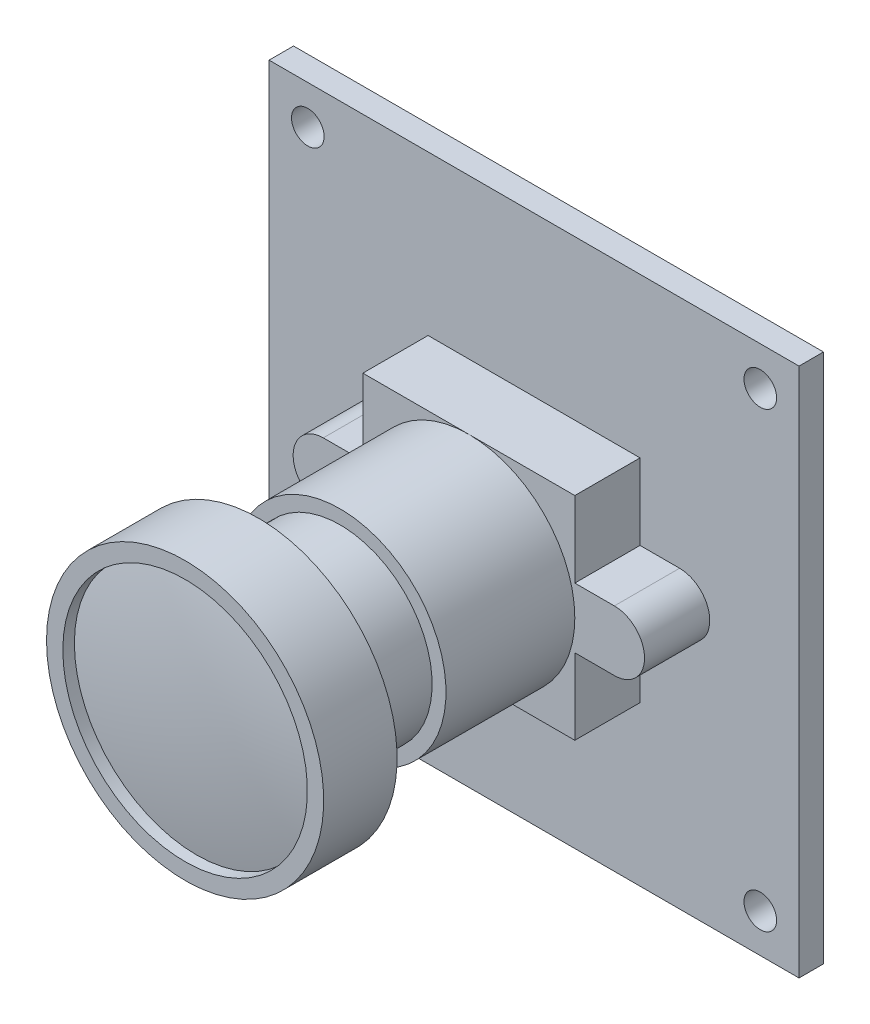
SolidWorks part; units mm, degrees
ref_plane "Front Plane" through (0, 0, 0) normal (0, 0, 1) x (1, 0, 0)
ref_plane "Top Plane" through (0, 0, 0) normal (0, 1, 0) x (1, 0, 0)
ref_plane "Right Plane" through (0, 0, 0) normal (1, 0, 0) x (0, 0, -1)
sketch "Sketch2" plane through (0, 0, 0) normal (0, 0, 1) x (1, 0, 0)
  line L1 (16.25, -16.25) -> (-16.25, -16.25)
  line L2 (16.25, -16.25) -> (16.25, 16.25)
  line L3 (16.25, 16.25) -> (-16.25, 16.25)
  line L4 (-16.25, -16.25) -> (-16.25, 16.25)
  line L5 (16.25, -16.25) -> (-16.25, 16.25) construction
  line L6 (16.25, 16.25) -> (-16.25, -16.25) construction
  line L7 (13.875, -13.875) -> (-13.875, -13.875) construction
  line L8 (13.875, -13.875) -> (13.875, 13.875) construction
  line L9 (13.875, 13.875) -> (-13.875, 13.875) construction
  line L10 (-13.875, -13.875) -> (-13.875, 13.875) construction
  line L11 (13.875, -13.875) -> (-13.875, 13.875) construction
  line L12 (13.875, 13.875) -> (-13.875, -13.875) construction
  circle A0 centre (13.875, 13.875) radius 1
  circle A1 centre (13.875, -13.875) radius 1
  circle A2 centre (-13.875, -13.875) radius 1
  circle A3 centre (-13.875, 13.875) radius 1
  point P0 (0, 0)
  point P6 (0, 0)
  dimension "D4" = 2
  dimension "D1" = 32.5
  dimension "D2" = 32.5
  dimension "D3" = 27.75
extrude "Boss-Extrude1" add sketch "Sketch2" along normal blind 1.5
sketch "Sketch4" plane through (0, 0, 1.5) normal (0, 0, 1) x (1, 0, 0)
  line L0 (8.925, 0) -> (-8.925, 0) construction
  line L1 (6.5, -6.5) -> (-6.5, -6.5)
  line L2 (6.5, -6.5) -> (6.5, 6.5)
  line L3 (6.5, 6.5) -> (-6.5, 6.5)
  line L4 (-6.5, -6.5) -> (-6.5, 6.5)
  line L5 (6.5, -6.5) -> (-6.5, 6.5) construction
  line L6 (6.5, 6.5) -> (-6.5, -6.5) construction
  line L7 (8.925, -1.85) -> (-8.925, -1.85)
  line L8 (8.925, 1.85) -> (-8.925, 1.85)
  arc A0 (8.925, -1.85) -> (8.925, 1.85) centre (8.925, 0) ccw
  arc A1 (-8.925, 1.85) -> (-8.925, -1.85) centre (-8.925, 0) ccw
  point P0 (0, 0)
  point P8 (0, 0)
  dimension "D4" = 1.85
  dimension "D1" = 13
  dimension "D2" = 13
  dimension "D3" = 17.85
extrude "Boss-Extrude2" add sketch "Sketch4" along normal blind 4 contours L2 L1 L4 L3 | L8 A1 L7 A0
sketch "Sketch5" plane through (0, 0, 0) normal (0, 1, 0) x (1, 0, 0)
  line L0 (0, 0) -> (0, -25.1637) construction
  line L1 (0, -5.5) -> (6.5, -5.5)
  line L2 (6.5, -5.5) -> (-6.5, -5.5) construction
  line L3 (6.5, -5.5) -> (6.5, -13.4)
  line L4 (6.5, -13.4) -> (5.65, -13.4)
  line L5 (5.65, -13.4) -> (5.65, -18.4)
  line L6 (5.65, -18.4) -> (8.5, -18.4)
  line L7 (8.5, -18.4) -> (8.5, -22.9)
  line L8 (8.5, -22.9) -> (7.5, -22.9)
  line L9 (0, -5.5) -> (0, -22.9)
  line L10 (7.5, -22.9) -> (7.5, -22.1906)
  line L11 (0, -22.9) -> (-0.8627, -22.9) construction
  arc A0 (7.5, -22.1906) -> (0, -22.9) centre (0, 17.1) cw
  point P16 (0, 0)
  point P18 (7.7785, -22.1364)
  dimension "D7" = 40
  dimension "D1" = 13
  dimension "D2" = 7.9
  dimension "D3" = 5
  dimension "D4" = 11.3
  dimension "D5" = 17
  dimension "D6" = 4.5
  dimension "D8" = 1
revolve "Revolve1" add sketch "Sketch5" angle 360 about L0
sketch "Sketch6" plane through (0, 0, 0) normal (0, 0, -1) x (-1, 0, 0)
  line L0 (-13.875, -13.875) -> (13.875, -13.875) construction
  line L1 (5, -16.25) -> (-5, -16.25)
  line L2 (5, -16.25) -> (5, -11.5)
  line L3 (5, -11.5) -> (-5, -11.5)
  line L4 (-5, -16.25) -> (-5, -11.5)
  line L5 (5, -16.25) -> (-5, -11.5) construction
  line L6 (5, -11.5) -> (-5, -16.25) construction
  point P0 (0, -13.875)
  dimension "D1" = 10
  dimension "D2" = 4.75
extrude "Boss-Extrude3" add sketch "Sketch6" along normal blind 6
